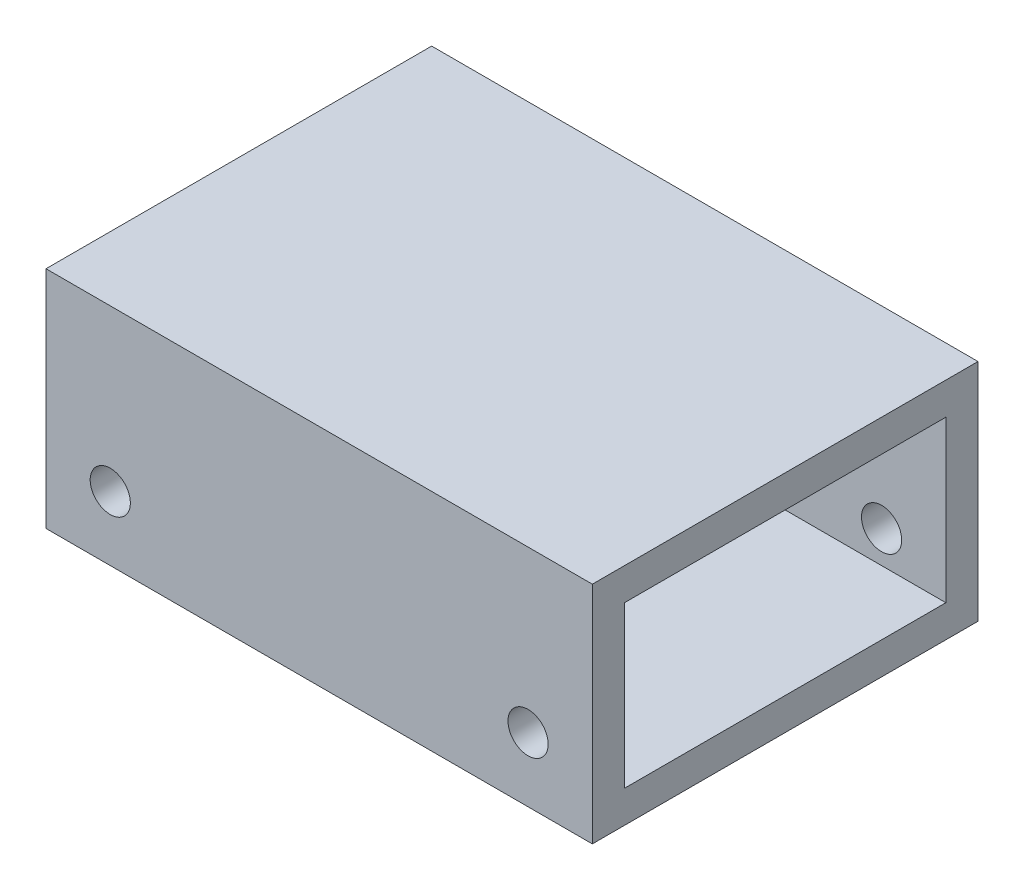
SolidWorks part; units mm, degrees
ref_plane "Front Plane" through (0, 0, 0) normal (0, 0, 1) x (1, 0, 0)
ref_plane "Top Plane" through (0, 0, 0) normal (0, 1, 0) x (1, 0, 0)
ref_plane "Right Plane" through (0, 0, 0) normal (1, 0, 0) x (0, 0, -1)
sketch "Sketch1" plane through (0, 0, 0) normal (0, 1, 0) x (1, 0, 0)
  line L1 (0, 0) -> (-215.9, 0)
  line L2 (0, 0) -> (0, 152.4)
  line L3 (0, 152.4) -> (-215.9, 152.4)
  line L4 (-215.9, 0) -> (-215.9, 152.4)
  line L5 (-215.9, 152.4) -> (-172.5636, 152.4)
  line L15 (-185.8756, 0) -> (0, 0)
  line L19 (-172.5636, 152.4) -> (0, 152.4)
  dimension "D1" = 152.4
  dimension "D2" = 215.9
extrude "Boss-Extrude1" add sketch "Sketch1" along normal blind 88.9 contours L4 L1 L2 L3
sketch "Sketch8" plane through (0, 88.9, 0) normal (0, 1, 0) x (1, 0, 0)
  line L0 (-215.9, 0) -> (-215.9, 152.4) construction
  line L1 (0, 152.4) -> (-215.9, 152.4) construction
  circle A0 centre (-107.95, 76.2) radius 27.4376
  dimension "D1" = 107.95
  dimension "D2" = 76.2
sketch "Sketch9" plane through (0, 0, 0) normal (1, 0, 0) x (0, 0, -1)
  line L0 (0, 88.9) -> (152.4, 88.9) construction
  line L1 (12.7, 76.2) -> (139.7, 76.2)
  line L2 (12.7, 76.2) -> (12.7, 12.7)
  line L3 (12.7, 12.7) -> (139.7, 12.7)
  line L4 (139.7, 76.2) -> (139.7, 12.7)
  line L5 (0, 88.9) -> (0, 0) construction
  line L7 (152.4, 88.9) -> (152.4, 0) construction
  line L8 (0, 0) -> (152.4, 0) construction
  dimension "D1" = 12.7
  dimension "D2" = 12.7
  dimension "D3" = 12.7
  dimension "D4" = 12.7
hole_wizard "5/8 (0.625) Diameter Hole1" positions "Sketch15" profile "Sketch16" hole size "5/8" standard "ANSI Inch" end condition through all
sketch "Sketch15" plane through (0, 0, 0) normal (0, 0, 1) x (1, 0, 0)
  line L0 (-215.9, 88.9) -> (-215.9, 0) construction
  line L1 (0, 0) -> (-215.9, 0) construction
  line L2 (0, 76.2) -> (0, 12.7) construction
  point P0 (-190.5, 25.4)
  point P2 (-25.4, 25.4)
  dimension "D1" = 25.4
  dimension "D2" = 25.4
  dimension "D3" = 25.4
  dimension "D4" = 25.4
sketch "Sketch16" plane through (-190.5, 25.4, 0) normal (1, 0, 0) x (0, -1, 0)
  line L0 (0, 0) -> (0, 152.4)
  line L1 (0, 152.4) -> (7.9375, 152.4)
  line L2 (7.9375, 152.4) -> (7.9375, 0)
  line L5 (7.9375, 0) -> (0, 0)
  line L11 (0, -6.35) -> (0, 107.95) construction
  dimension "Thru Hole Dia." = 15.875
  dimension "Thru Hole Depth" = 152.4
extrude "Cut-Extrude1" cut sketch "Sketch9" against normal through all contours L2 L1 L4 L3
